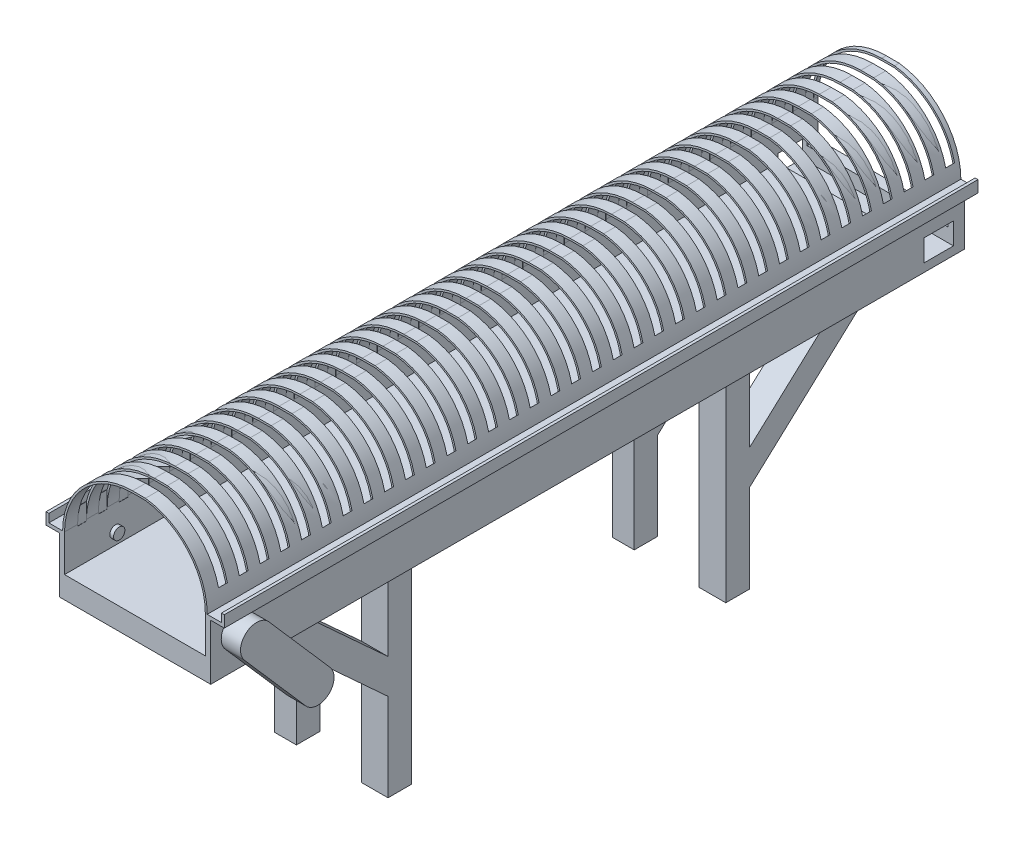
SolidWorks part; units mm, degrees
ref_plane "Alzado" through (0, 0, 0) normal (0, 0, 1) x (1, 0, 0)
ref_plane "Planta" through (0, 0, 0) normal (0, 1, 0) x (1, 0, 0)
ref_plane "Vista lateral" through (0, 0, 0) normal (1, 0, 0) x (0, 0, -1)
sketch "Croquis1" plane through (0, 0, 0) normal (0, 1, 0) x (1, 0, 0)
  line L1 (-400, 1995) -> (400, 1995)
  line L2 (-400, 1995) -> (-400, -1995)
  line L3 (-400, -1995) -> (400, -1995)
  line L4 (400, 1995) -> (400, -1995)
  line L5 (-400, 1995) -> (400, -1995) construction
  line L6 (-400, -1995) -> (400, 1995) construction
  point P0 (0, 0)
  dimension "D1" = 800
  dimension "D2" = 3990
extrude "Saliente-Extruir1" add sketch "Croquis1" along normal blind 340
sketch "Croquis2" plane through (0, 0, 1995) normal (0, 0, 1) x (1, 0, 0)
  line L0 (-400, 293.8335) -> (-472.0725, 293.8335)
  line L1 (-400, 340) -> (-400, 0) construction
  line L2 (-472.0725, 293.8335) -> (-472.0725, 355.4082)
  line L3 (-472.0725, 355.4082) -> (-457.0209, 355.4082)
  line L4 (-457.0209, 355.4082) -> (-457.0209, 311.6218)
  line L5 (-457.0209, 311.6218) -> (-400, 311.6218)
  line L6 (0, 0) -> (0, 11.9583) construction
  line L7 (457.0209, 311.6218) -> (400, 311.6218)
  line L8 (457.0209, 355.4082) -> (457.0209, 311.6218)
  line L9 (472.0725, 355.4082) -> (457.0209, 355.4082)
  line L10 (472.0725, 293.8335) -> (472.0725, 355.4082)
  line L11 (400, 293.8335) -> (472.0725, 293.8335)
  line L12 (400, 311.6218) -> (400, 293.8335)
  line L13 (-400, 311.6218) -> (-400, 293.8335)
extrude "Saliente-Extruir2" add sketch "Croquis2" against normal blind 3990
sketch "Croquis3" plane through (0, 0, 1995) normal (0, 0, 1) x (1, 0, 0)
  line L0 (-400, 311.6218) -> (-374.0553, 311.6218)
  line L1 (-374.0553, 311.6218) -> (-374.0553, 116.1771)
  line L2 (-374.0553, 116.1771) -> (371.3774, 116.1771)
  line L3 (371.3774, 116.1771) -> (371.3774, 311.6218)
  line L4 (371.3774, 311.6218) -> (400.0016, 311.6218)
  line L5 (400.0016, 311.6218) -> (400, 340)
  line L6 (400, 340) -> (-400, 340)
  line L7 (-400, 340) -> (-400, 311.6218)
extrude "Cortar-Extruir1" cut sketch "Croquis3" against normal blind 3990
sketch "Croquis4" plane through (0, 0, 1995) normal (0, 0, 1) x (1, 0, 0)
  line L0 (371.3774, 116.1771) -> (371.3774, 311.6218) construction
  line L1 (53.7439, 670.3557) -> (-14.0489, 670.3557)
  line L2 (-1.339, 116.1771) -> (-1.339, 670.3557) construction
  line L3 (-374.0553, 116.1771) -> (371.3774, 116.1771) construction
  line L4 (54.3474, 680.3557) -> (-14.0489, 680.3557)
  line L5 (371.3774, 311.6218) -> (381.3774, 311.6218)
  line L6 (381.3774, 311.6218) -> (381.4697, 311.5162)
  line L7 (-384.0553, 311.6572) -> (-384.0553, 311.6218)
  line L8 (-374.0553, 311.6218) -> (-457.0209, 311.6218) construction
  line L9 (-384.0553, 311.6218) -> (-374.0553, 311.6218)
  arc A0 (371.3774, 311.6218) -> (53.7439, 670.3557) centre (9.9843, 311.6218) ccw
  arc A1 (-14.0489, 670.3557) -> (-374.0553, 311.6218) centre (-14.0489, 310.3471) ccw
  arc A2 (381.3774, 311.6218) -> (54.3474, 680.3557) centre (9.9843, 311.6218) ccw
  arc A3 (-14.0489, 680.3557) -> (-384.0553, 311.6572) centre (-14.0489, 310.3471) ccw
  point P10 (-140.9666, 570.3557)
  point P25 (159.0188, 570.3557)
  point P26 (135.4598, 580.3557)
  point P27 (80.4336, 570.3557)
  point P28 (-80.0266, 570.3557)
  point P29 (77.4232, 620.3557)
  point P30 (102.8132, 670.3557)
  point P31 (-67.7148, 670.3557)
  point P32 (40.807, 670.3557)
  point P33 (-22.1612, 680.3557)
  point P34 (12.3981, 670.3557)
  point P35 (58.1313, 670.3557)
  point P36 (-33.4861, 670.3557)
  point P37 (82.5674, 670.3557)
  point P38 (21.0112, 670.3557)
  point P39 (54.3474, 670.3557)
  point P40 (-14.0489, 670.3557)
  line M3 (457.0209, 311.6218) -> (371.3774, 311.6218)
  line M7 (-374.0553, 311.6218) -> (-457.0209, 311.6218)
  dimension "D2" = 554.1786
  dimension "D1" = 10
extrude "Saliente-Extruir4" add sketch "Croquis4" against normal blind 3990 contours L4 A3 L7 A1 L1 A0 A2 M7 M3
sketch "Croquis5" plane through (0, 680.3557, 0) normal (0, 1, 0) x (1, 0, 0)
  line L1 (372.1051, -1925.86) -> (-374.8866, -1925.86)
  line L2 (372.1051, -1925.86) -> (372.1051, -1879.0082)
  line L3 (372.1051, -1879.0082) -> (-374.8866, -1879.0082)
  line L4 (-374.8866, -1925.86) -> (-374.8866, -1879.0082)
  line L5 (372.1051, -1925.86) -> (-374.8866, -1879.0082) construction
  line L6 (372.1051, -1879.0082) -> (-374.8866, -1925.86) construction
  point P0 (-1.3908, -1902.4341)
  point P5 (-372.2748, -1924.554)
  point P6 (372.1051, -1921.9422)
  point P7 (-374.8866, -1925.86)
extrude "Cortar-Extruir2" cut sketch "Croquis5" against normal blind 377
pattern_linear "MatrizL1" count 36 spacing 110 along (0, 0, -1) of "Cortar-Extruir2"
sketch "Croquis6" plane through (-400, 0, 0) normal (-1, 0, 0) x (0, 0, 1)
  circle A0 centre (-250.3023, 144.3274) radius 30
  dimension "D1" = 60
sketch3d "Croquis3D1"
  line L0 (-400, 144.3274, -250.3023) -> (-444.6231, 144.3274, -250.3023)
  line L1 (-494.6231, 134.1678, -201.3453) -> (-494.6231, -59.0147, 729.5554)
  line L2 (-494.6231, -56.0986, 759.2147) -> (-494.6231, 175.6298, 1306.3513)
  line L3 (-494.6231, 179.5889, 1325.851) -> (-494.6231, 179.5889, 1675.3745)
  line L4 (-444.6231, 179.5889, 1725.3745) -> (-354.1056, 179.5889, 1725.3745)
  arc A0 (-494.6231, 179.5889, 1675.3745) -> (-444.6231, 179.5889, 1725.3745) centre (-444.6231, 179.5889, 1675.3745) ccw
  arc A1 (-494.6231, 175.6298, 1306.3513) -> (-494.6231, 179.5889, 1325.851) centre (-494.6231, 129.5889, 1325.851) ccw
  arc A2 (-494.6231, -59.0147, 729.5554) -> (-494.6231, -56.0986, 759.2147) centre (-494.6231, -10.0577, 739.715) ccw
  arc A3 (-444.6231, 144.3274, -250.3023) -> (-494.6231, 134.1678, -201.3453) centre (-444.6231, 134.1678, -201.3453) ccw
  point P9 (-494.6231, 179.5889, 1725.3745)
  point P10 (-444.6231, 229.5889, 1675.3745)
  point P13 (-494.6231, 179.5889, 1315.6992)
  point P14 (-444.6231, 129.5889, 1325.851)
  point P17 (-494.6231, -62.1866, 744.8403)
  point P18 (-544.6231, -10.0577, 739.715)
  point P21 (-494.6231, 144.3274, -250.3023)
  point P22 (-444.6231, 183.1247, -191.1857)
  dimension "D1" = 50
sweep "Barrer2" add profiles "Croquis6" path "Croquis3D1"
sketch "Croquis7" plane through (-400, 0, 0) normal (-1, 0, 0) x (0, 0, 1)
  line L1 (-1937.1375, 158.8972) -> (-1781.5774, 158.8972)
  line L2 (-1937.1375, 158.8972) -> (-1937.1375, 44.0789)
  line L3 (-1937.1375, 44.0789) -> (-1781.5774, 44.0789)
  line L4 (-1781.5774, 158.8972) -> (-1781.5774, 44.0789)
  line L5 (-1937.1375, 158.8972) -> (-1781.5774, 44.0789) construction
  line L6 (-1937.1375, 44.0789) -> (-1781.5774, 158.8972) construction
  point P0 (-1859.3574, 101.4881)
extrude "Cortar-Extruir3" cut sketch "Croquis7" against normal blind 971
sketch "Croquis8" plane through (400, 0, 0) normal (1, 0, 0) x (0, 0, -1)
  line L0 (-1853.9721, 179.1851) -> (-1529.5743, -192.2268) construction
  line L1 (-1789.662, 235.3547) -> (-1465.2642, -136.0572)
  line L2 (-1918.2822, 123.0155) -> (-1593.8844, -248.3964)
  arc A0 (-1789.662, 235.3547) -> (-1918.2822, 123.0155) centre (-1853.9721, 179.1851) ccw
  arc A1 (-1593.8844, -248.3964) -> (-1465.2642, -136.0572) centre (-1529.5743, -192.2268) ccw
  point P2 (-1691.7732, -6.5208)
extrude "Saliente-Extruir5" add sketch "Croquis8" along normal blind 102
ref_plane "Plano1" through (0, 0, 0) normal (1, 0, 0) x (0, 0, -1)
sketch "Croquis9" plane through (0, 0, 0) normal (1, 0, 0) x (0, 0, -1)
  line L0 (0, 680.3557) -> (0, -919.6443) construction
  line L1 (54.14, 680.3557) -> (-9.0082, 680.3557) construction
  line L2 (1637.2948, 0) -> (956.444, -624.2981)
  line L3 (1995, 0) -> (-1995, 0) construction
  line L4 (956.444, -624.2981) -> (956.444, -1089.6443)
  line L5 (956.444, -1089.6443) -> (831.8981, -1089.6443)
  line L6 (831.8981, -1089.6443) -> (831.8981, 0)
  line L7 (831.8981, 0) -> (956.444, 0)
  line L8 (956.444, 0) -> (956.444, -441.6308)
  line L9 (956.444, -441.6308) -> (1438.0804, 0)
  line L10 (1438.0804, 0) -> (1637.2948, 0)
  line L11 (-1438.0804, 0) -> (-1637.2948, 0)
  line L12 (-956.444, -441.6308) -> (-1438.0804, 0)
  line L13 (-956.444, 0) -> (-956.444, -441.6308)
  line L14 (-831.8981, 0) -> (-956.444, 0)
  line L15 (-831.8981, -1089.6443) -> (-831.8981, 0)
  line L16 (-956.444, -1089.6443) -> (-831.8981, -1089.6443)
  line L17 (-956.444, -624.2981) -> (-956.444, -1089.6443)
  line L18 (-1637.2948, 0) -> (-956.444, -624.2981)
  dimension "D1" = 1600
extrude "Saliente-Extruir6" add sketch "Croquis9" along normal blind 300 and the other way blind 300
sketch "Croquis10" plane through (0, 0, -1995) normal (0, 0, -1) x (-1, 0, 0)
  line L0 (-158.7133, -56.7601) -> (-158.7133, -1268.8886)
  line L1 (-158.7133, -1268.8886) -> (184.8312, -1268.8886)
  line L2 (184.8312, -1268.8886) -> (184.8312, -56.7601)
  line L3 (184.8312, -56.7601) -> (-158.7133, -56.7601)
extrude "Cortar-Extruir4" cut sketch "Croquis10" against normal blind 4000
sketch "Croquis11" plane through (300, 0, 0) normal (1, 0, 0) x (0, 0, -1)
  line L0 (-1409.0154, -85.5436) -> (-1441.7215, -114.9791)
  line L1 (-1441.7215, -114.9791) -> (-995.943, -544.513)
